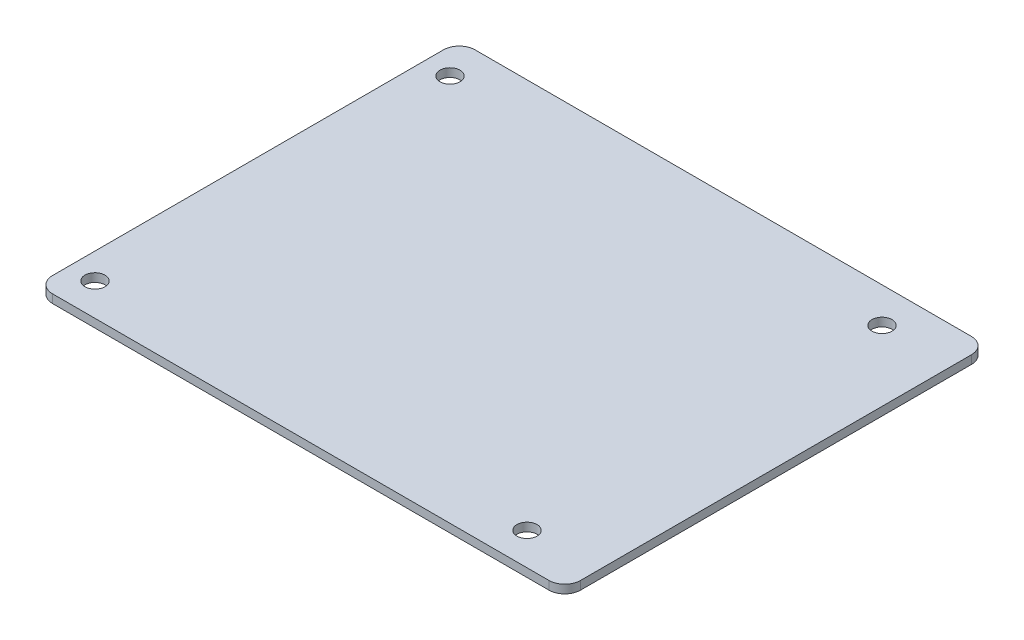
SolidWorks part; units mm, degrees
ref_plane "Front Plane" through (0, 0, 0) normal (0, 0, 1) x (1, 0, 0)
ref_plane "Top Plane" through (0, 0, 0) normal (0, 1, 0) x (1, 0, 0)
ref_plane "Right Plane" through (0, 0, 0) normal (1, 0, 0) x (0, 0, -1)
sketch "Sketch1" plane through (0, 0, 0) normal (0, 1, 0) x (1, 0, 0)
  line L1 (50.06, -40.06) -> (-50.06, -40.06)
  line L2 (50.06, -40.06) -> (50.06, 40.06)
  line L3 (50.06, 40.06) -> (-50.06, 40.06)
  line L4 (-50.06, -40.06) -> (-50.06, 40.06)
  line L5 (50.06, -40.06) -> (-50.06, 40.06) construction
  line L6 (50.06, 40.06) -> (-50.06, -40.06) construction
  point P0 (0, 0)
  dimension "D1" = 100.12
  dimension "D2" = 80.12
extrude "Boss-Extrude1" add sketch "Sketch1" along normal mid plane 1.6
fillet "Fillet1" radius 3 4 edges at (-50.06, 0, -40.06) (50.06, 0, -40.06) (50.06, 0, 40.06) (-50.06, 0, 40.06)
sketch "Sketch2" plane through (0, 0.8, 0) normal (0, 1, 0) x (1, 0, 0)
  line L0 (-50.06, 37.06) -> (-50.06, -37.06) construction
  line L2 (47.06, 40.06) -> (-47.06, 40.06) construction
  line L4 (36.76, -33.9175) -> (-45.155, -33.9175) construction
  line L5 (36.76, -33.9175) -> (36.76, 33.3925) construction
  line L6 (36.76, 33.3925) -> (-45.155, 33.3925) construction
  line L7 (-45.155, -33.9175) -> (-45.155, 33.3925) construction
  line L8 (36.76, -33.9175) -> (-45.155, 33.3925) construction
  line L9 (36.76, 33.3925) -> (-45.155, -33.9175) construction
  circle A0 centre (-45.155, 33.3925) radius 1.905
  circle A1 centre (-45.155, -33.9175) radius 1.905
  circle A2 centre (36.76, -33.9175) radius 1.905
  circle A3 centre (36.76, 33.3925) radius 1.905
  point P8 (-47.06, 33.3925)
  point P11 (-45.155, 35.2975)
  point P14 (-45.8745, 33.3925)
  point P15 (-45.155, -34.5668)
  point P16 (-4.1975, -0.2625)
  point P17 (34.841, 33.3925)
  point P19 (34.841, -33.9175)
  dimension "D1" = 3.81
  dimension "D2" = 3
  dimension "D3" = 4.7625
  dimension "D4" = 67.31
  dimension "D5" = 81.915
extrude "Cut-Extrude1" cut sketch "Sketch2" against normal up to next
